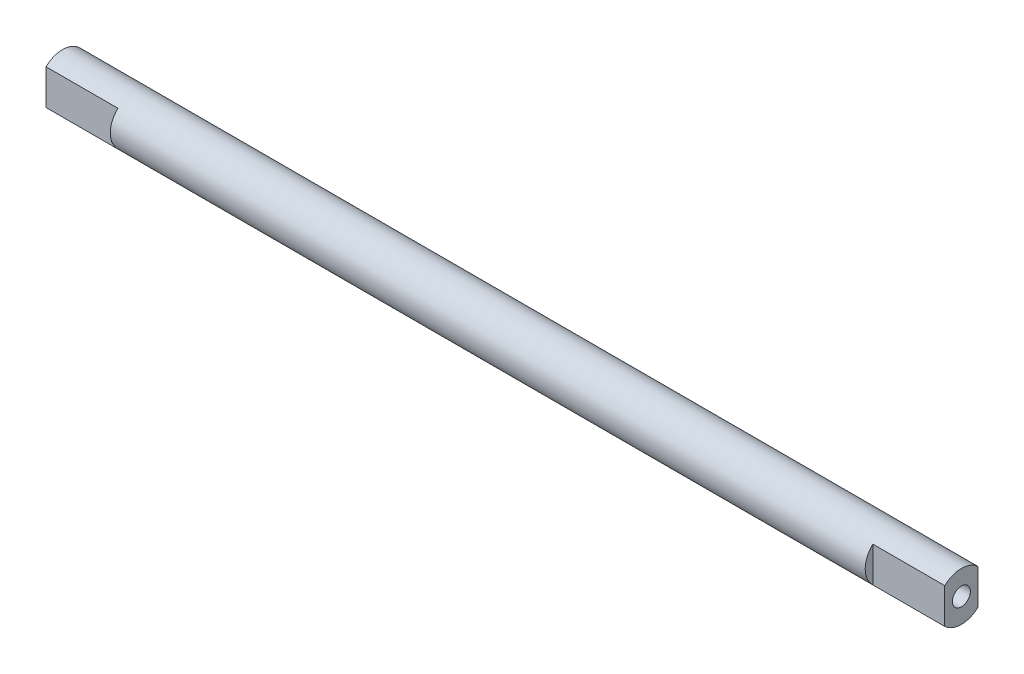
SolidWorks part; units mm, degrees
ref_plane "Front Plane" through (0, 0, 0) normal (0, 0, 1) x (1, 0, 0)
ref_plane "Top Plane" through (0, 0, 0) normal (0, 1, 0) x (1, 0, 0)
ref_plane "Right Plane" through (0, 0, 0) normal (1, 0, 0) x (0, 0, -1)
sketch "Sketch1" plane through (0, 0, 0) normal (1, 0, 0) x (0, 0, -1)
  circle A0 centre (0, 0) radius 2.7
  dimension "D1" = 5.4
extrude "Boss-Extrude1" add sketch "Sketch1" along normal mid plane 100
sketch "Sketch2" plane through (50, 0, 0) normal (1, 0, 0) x (0, 0, -1)
  line L0 (-1.85, 1.9666) -> (-1.85, -1.9666)
  line L1 (1.85, 1.9666) -> (1.85, -1.9666)
  arc A0 (-1.85, 1.9666) -> (-1.85, -1.9666) centre (0, 0) ccw
  arc A1 (1.85, -1.9666) -> (1.85, 1.9666) centre (0, 0) ccw
  dimension "D3" = 5.4
  dimension "D1" = 3.7
  dimension "D2" = 1.85
extrude "Cut-Extrude1" cut sketch "Sketch2" against normal blind 8
sketch "Sketch3" plane through (50, 0, 0) normal (1, 0, 0) x (0, 0, -1)
  circle A0 centre (0, 0) radius 1
  dimension "D1" = 2
extrude "Cut-Extrude2" cut sketch "Sketch3" against normal blind 6
mirror "Mirror1" about plane through (0, 0, 0) normal (1, 0, 0) of "Cut-Extrude1", "Cut-Extrude2"
